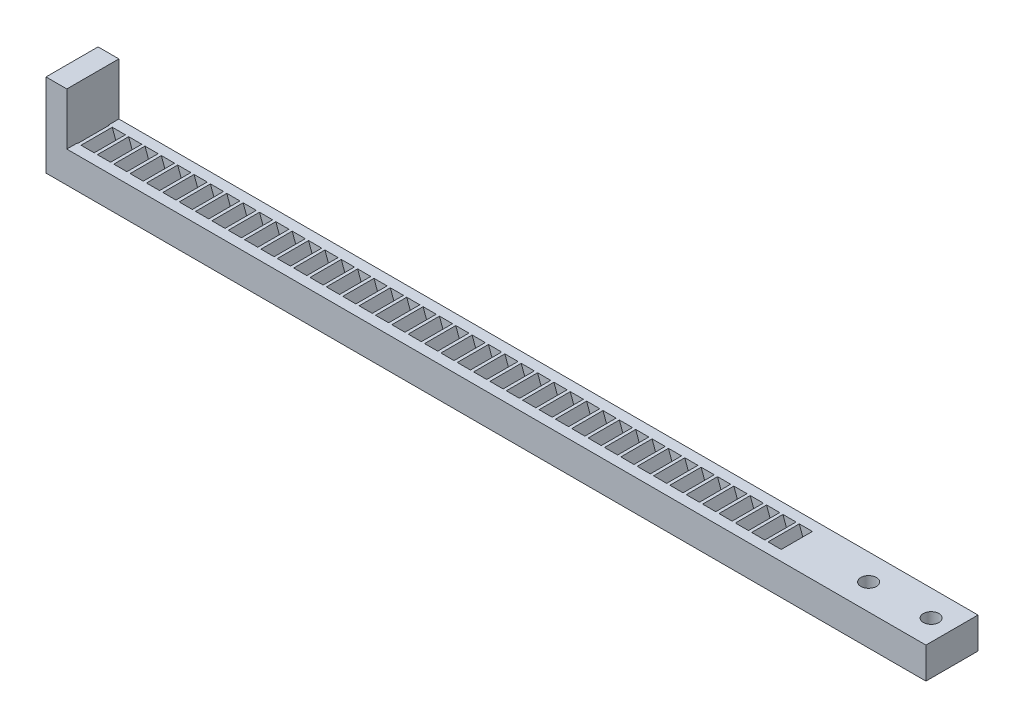
SolidWorks part; units mm, degrees
extrude "Blank" add sketch "BlankSke" against normal blind 6
sketch "BlankSke" plane through (0, 0, 0) normal (0, 0, 1) x (1, 0, 0)
  line L1 (0, 0) -> (185, 0)
  line L2 (0, 0) -> (0, 6)
  line L3 (0, 6) -> (185, 6)
  line L4 (185, 0) -> (185, 6)
  dimension "Length" = 185
  dimension "Blank_height" = 6
ref_plane "Plane1" through (0, 0, 0) normal (0, 0, 1) x (1, 0, 0)
ref_plane "Plane2" through (0, 0, 0) normal (0, 1, 0) x (1, 0, 0)
ref_plane "Plane3" through (0, 0, 0) normal (1, 0, 0) x (0, 0, -1)
sketch "HoldingSke" plane through (0, 0, 0) normal (0, 1, 0) x (1, 0, 0)
  line L0 (0, 0) -> (0.1392, 0.9903)
  line L1 (-15, 0) -> (100, 0) construction
  line L2 (0, 0) -> (-2.1039, 2.3779)
  line L3 (0, 0) -> (-11.863, 4.5341)
  line L4 (0, 0) -> (7.2428, 4.7035)
  line L5 (0, 0) -> (-23.7986, -8.8762)
  line L6 (0, 0) -> (-10.5278, -7.1032)
  line L9 (-71.009, 38.7566) -> (22.9603, 72.9586)
  line L10 (-76.2, 3.3779) -> (-71.2, 3.3779)
  line L11 (0, 0) -> (-6, 0)
  line L12 (-76.2, 101.6) -> (-76.162, 101.6)
  line L13 (24.9733, 27.94) -> (52.9518, 28.4284)
  line L14 (24.9733, 27.94) -> (24.9743, 27.94)
  line L15 (24.9733, 27.94) -> (100.4006, 29.5858)
  circle A0 centre (0, 0) radius 19.05
  circle A1 centre (0, 0) radius 2.5
  circle A2 centre (0, 0) radius 12.7
  dimension "MPH" = 5
  dimension "Diameter" = 38.1
  dimension "Num_teeth" = 33
  dimension "Pitch" = 1
  dimension "Show_teeth" = 998
  dimension "Thickness" = 12.7
  dimension "Ap" = 20
  dimension "Pitch_height" = 5
  dimension "Width" = 6
  dimension "Backlash" = 0.038
  dimension "Addendum_fac" = 1
  dimension "Dedendum_fac" = 1.25
  dimension "Clearance_fac" = 0.25
  dimension "Dedendum_add" = 0.001
  dimension "Length" = 100
  dimension "Module" = 1
sketch "TooCutSkeIll" plane through (0, 0, 0) normal (0, 0, 1) x (1, 0, 0)
  line L0 (-1.2538, 5.9737) -> (-0.5045, 3.9152)
  line L1 (-0.2687, 3.75) -> (0.2687, 3.75)
  line L2 (0.5045, 3.9152) -> (1.2538, 5.9737)
  line L3 (185, 6) -> (0, 6) construction
  line L4 (0, 0) -> (0, 64.897) construction
  line L5 (-13.208, 5) -> (12.954, 5) construction
  line L6 (0, 0) -> (185, 0) construction
  line L7 (0.8994, 5) -> (0.8994, 48.7463) construction
  line L8 (-0.8994, 5) -> (-0.8994, 48.7463) construction
  line L9 (1.2914, 6) -> (1.2914, 6.0254)
  line L10 (-1.2914, 6) -> (-1.2914, 6.0254)
  line L11 (-1.2914, 6.0254) -> (1.2914, 6.0254)
  arc A0 (0.2687, 3.75) -> (0.5045, 3.9152) centre (0.2687, 4.001) ccw
  arc A1 (-0.5045, 3.9152) -> (-0.2687, 3.75) centre (-0.2687, 4.001) ccw
  arc A2 (1.2914, 6) -> (1.2538, 5.9737) centre (1.2914, 5.96) ccw
  arc A3 (-1.2538, 5.9737) -> (-1.2914, 6) centre (-1.2914, 5.96) ccw
  dimension "Pitch_height" = 5
  dimension "Addendum_plus" = 1.0254
  dimension "Pressure_angle" = 20
  dimension "Gap_width" = 1.7988
  dimension "Dedendum" = 1.25
extrude "ToothCutIll" cut sketch "TooCutSkeIll" against normal through all
sketch "TooCutSkeSim" plane through (0, 0, 0) normal (0, 0, 1) x (1, 0, 0)
  line L0 (0.4444, 3.75) -> (-0.4444, 3.75)
  line L1 (1.2726, 6.0254) -> (0.4444, 3.75)
  line L2 (0, 17.4625) -> (0, 53.467) construction
  line L3 (1.2726, 6.0254) -> (-1.2726, 6.0254)
  line L6 (-1.2726, 6.0254) -> (-0.4444, 3.75)
  line L9 (-0.8994, 5) -> (0.8994, 5) construction
  line L10 (0, 0) -> (185, 0) construction
  line L11 (0.8994, 5) -> (0.8994, 53.467) construction
  line L12 (-0.8994, 5) -> (-0.8994, 53.467) construction
  dimension "Pitch_height" = 5
  dimension "Addendum_plus" = 1.0254
  dimension "Pressure_angle" = 20
  dimension "Gap_width" = 1.7988
  dimension "Dedendum" = 1.25
extrude "ToothCutSim" cut sketch "TooCutSkeSim" against normal through all
pattern_linear "TeethCuts" [suppressed]
pattern_linear "Линейный массив1" count 50 spacing 3.1416 along (1, 0, 0) of "ToothCutSim"
sketch "Эскиз1" plane through (185, 0, 0) normal (1, 0, 0) x (0, 0, -1)
  line L1 (0, 0) -> (5.0003, 0)
  line L2 (0, 0) -> (0, -10)
  line L3 (0, -10) -> (6, -10)
  line L4 (6, 0) -> (6, -10)
  line L5 (6, 6) -> (0, 6) construction
  line L7 (6, 5.9737) -> (5.0003, 6)
  line L8 (5.0003, 6) -> (5.0003, 0)
  line L9 (6, 5.9737) -> (6, 0)
  point P6 (-0.1352, 0)
sketch "Эскиз3" plane through (0, 0, 0) normal (-1, 0, 0) x (0, 0, 1)
  line L1 (-6, 0) -> (0, 0)
  line L2 (-6, 0) -> (-6, 6)
  line L3 (-6, 6) -> (0, 6)
  line L4 (0, 0) -> (0, 6)
extrude "Вырез-Вытянуть1" cut sketch "Эскиз3" against normal blind 16
sketch "Эскиз2" plane through (185, 0, 0) normal (1, 0, 0) x (0, 0, -1)
  line L1 (6, 6) -> (8, 6)
  line L2 (6, 6) -> (6, 0)
  line L3 (6, 0) -> (8, 0)
  line L4 (8, 6) -> (8, 0)
  line L5 (0, 6) -> (-2, 6)
  line L6 (0, 6) -> (0, 0)
  line L7 (0, 0) -> (-2, 0)
  line L8 (-2, 6) -> (-2, 0)
extrude "Бобышка-Вытянуть2" add sketch "Эскиз2" against normal up to surface (169 mm away) up to face at (16, 1.875, -3)
sketch "Эскиз4" plane through (16, 0, 0) normal (-1, 0, 0) x (0, 0, 1)
  line L1 (-4.6, 1.6) -> (-4.6, 0)
  line L2 (-8, 0) -> (2, 0) construction
  line L3 (-4.6, 0) -> (-1.4, 0)
  line L4 (-1.4, 0) -> (-1.4, 1.6)
  arc A1 (-1.4, 1.6) -> (-4.6, 1.6) centre (-3, 1.6) ccw
extrude "Вырез-Вытянуть2" cut sketch "Эскиз4" against normal blind 150
sketch "Эскиз5" plane through (16, 0, 0) normal (-1, 0, 0) x (0, 0, 1)
  line L1 (-8, 0) -> (2, 0)
  line L2 (-8, 0) -> (-8, 16)
  line L3 (-8, 16) -> (2, 16)
  line L4 (2, 0) -> (2, 16)
extrude "Бобышка-Вытянуть3" add sketch "Эскиз5" against normal blind 4
sketch "Эскиз6" plane through (0, 6, 0) normal (0, 1, 0) x (1, 0, 0)
  circle A2 centre (181, 3) radius 1.5
  circle A3 centre (169, 3) radius 1.5
extrude "Вырез-Вытянуть3" cut sketch "Эскиз6" against normal through all
equation "' \"Module@HoldingSke\" = 6.35"
equation "' \"Num_teeth@HoldingSke\" = 12"
equation "' \"Ap@HoldingSke\" =  20"
equation "' \"Ap@HoldingSke\" = 20"
equation "' \"Width@HoldingSke\" = 0.25 * 25.4"
equation "' \"Show_teeth@HoldingSke\" = 500"
equation "' \"Backlash@HoldingSke\" = 0.009 * 25.4"
equation "' \"Addendum_fac@HoldingSke\" = 1.0"
equation "' \"Dedendum_fac@HoldingSke\" = 1.25"
equation "' \"Dedendum_add@HoldingSke\" = 0.00005 * 25.4"
equation "' \"Clearance_fac@HoldingSke\" = 0.25"
equation "' \"Pitch_height@HoldingSke\" = 1 * 25.4"
equation "' \"Length@HoldingSke\" = 4.71 * 25.4"
equation "\"Pitch@HoldingSke\" = 1 / \"Module@HoldingSke\""
equation "\"MPH@HoldingSke\" = \"Dedendum_fac@HoldingSke\" / \"Pitch@HoldingSke\" + 2 * \"Dedendum_add@HoldingSke\" + 0.002 * 25.4"
equation "\"MPH@HoldingSke\" = ((sgn( \"MPH@HoldingSke\" - \"Pitch_height@HoldingSke\")+1)*( \"MPH@HoldingSke\" - \"Pitch_height@HoldingSke\"))/2 + \"Pitch_height@HoldingSke\""
equation "\"Blank_height@BlankSke\" = \"Pitch_height@HoldingSke\" + \"Addendum_fac@HoldingSke\"  / \"Pitch@HoldingSke\" "
equation "\"Length@BlankSke\"=\"Length@HoldingSke\"+85"
equation "\"Face_width@Blank\" = \"Width@HoldingSke\""
equation "\"Pressure_angle@TooCutSkeIll\" = \"Ap@HoldingSke\""
equation "\"Addendum_plus@TooCutSkeIll\" =  \"Addendum_fac@HoldingSke\"  / \"Pitch@HoldingSke\" + 0.001 *25.4"
equation "\"Dedendum@TooCutSkeIll\" = \"Dedendum_fac@HoldingSke\"  / \"Pitch@HoldingSke\""
equation "\"Pitch_height@TooCutSkeIll\" =  \"MPH@HoldingSke\""
equation "\"Gap_width@TooCutSkeIll\" = 3.14159265 / 2 / \"Pitch@HoldingSke\" + 6 * \"Backlash@HoldingSke\""
equation "\"Pressure_angle@TooCutSkeSim\" = \"Ap@HoldingSke\""
equation "\"Addendum_plus@TooCutSkeSim\" =  \"Addendum_fac@HoldingSke\"  / \"Pitch@HoldingSke\" + 0.001 * 25.4"
equation "\"Dedendum@TooCutSkeSim\" = \"Dedendum_fac@HoldingSke\"  / \"Pitch@HoldingSke\""
equation "\"Pitch_height@TooCutSkeSim\" =  \"MPH@HoldingSke\""
equation "\"Gap_width@TooCutSkeSim\" = 3.14159265 / 2 / \"Pitch@HoldingSke\" + 6 * \"Backlash@HoldingSke\""
equation "\"Root_fillet@TooCutSkeIll\" = \"Clearance_fac@HoldingSke\" / \"Pitch@HoldingSke\" + \"Dedendum_add@HoldingSke\""
equation "\"Break_rad@TooCutSkeIll\" = 0.02 / \"Pitch@HoldingSke\" * 2"
equation "\"Linear_pitch@TeethCuts\" = 3.14159265 / \"Pitch@HoldingSke\""
equation "\"Num_teeth@HoldingSke\" = int( ( \"Length@HoldingSke\" + 0 ) / (3.14159265 / \"Pitch@HoldingSke\")) + 0.9999  + 1"
equation "\"Num_teeth@TeethCuts\"=40"
equation " \"Num_teeth@TeethCuts\" = ((sgn( \"Num_teeth@TeethCuts\" - \"Num_teeth@HoldingSke\" )-1)*( \"Num_teeth@TeethCuts\" - \"Num_teeth@HoldingSke\" ))/-2+ \"Num_teeth@HoldingSke\""
equation " \"Num_teeth@TeethCuts\" = ((sgn( \"Num_teeth@TeethCuts\" - 2.0)+1)*( \"Num_teeth@TeethCuts\" - 2.0))/2 +2.0"
equation "\"D3@Линейный массив1\"=3.14159265 / \"Pitch@HoldingSke\""
